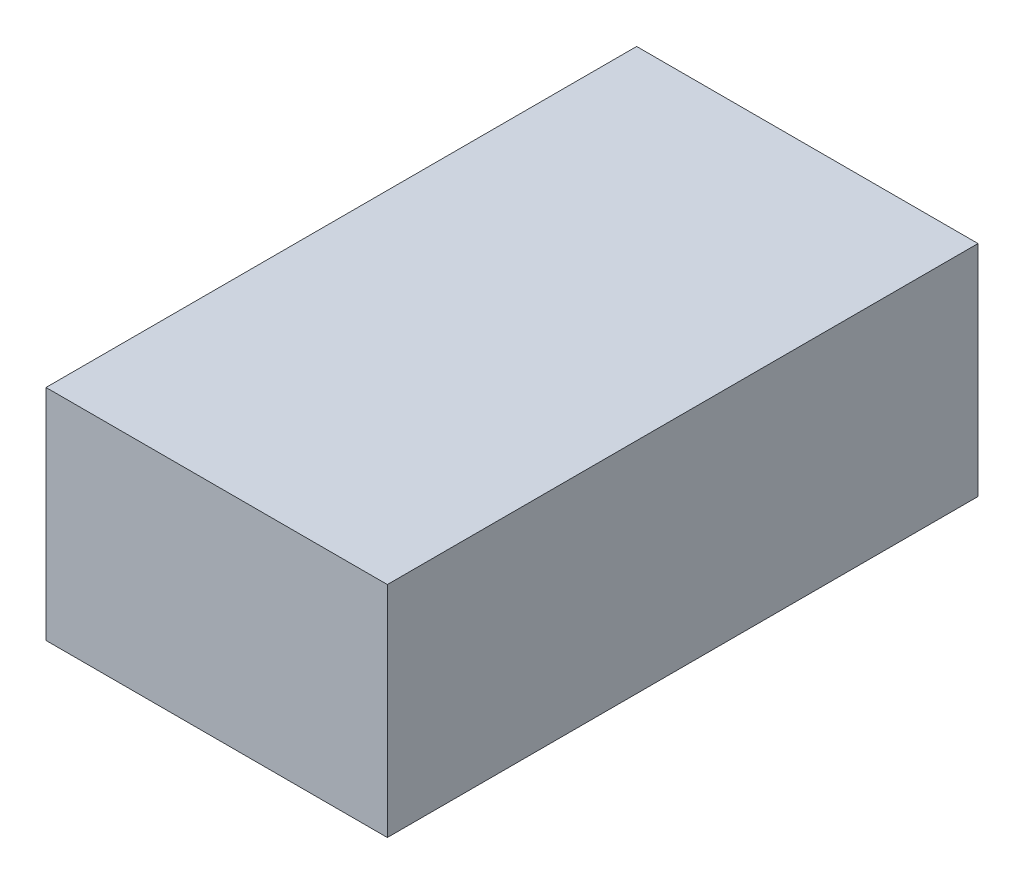
SolidWorks part; units mm, degrees
ref_plane "Front Plane" through (0, 0, 0) normal (0, 0, 1) x (1, 0, 0)
ref_plane "Top Plane" through (0, 0, 0) normal (0, 1, 0) x (1, 0, 0)
ref_plane "Right Plane" through (0, 0, 0) normal (1, 0, 0) x (0, 0, -1)
sketch "Sketch1" plane through (0, 0, 0) normal (0, 1, 0) x (1, 0, 0)
  line L1 (-89.8733, 29.7379) -> (-50.3027, 29.7379)
  line L2 (-89.8733, 29.7379) -> (-89.8733, -38.7312)
  line L3 (-89.8733, -38.7312) -> (-50.3027, -38.7312)
  line L4 (-50.3027, 29.7379) -> (-50.3027, -38.7312)
extrude "Boss-Extrude1" add sketch "Sketch1" along normal blind 25.4
